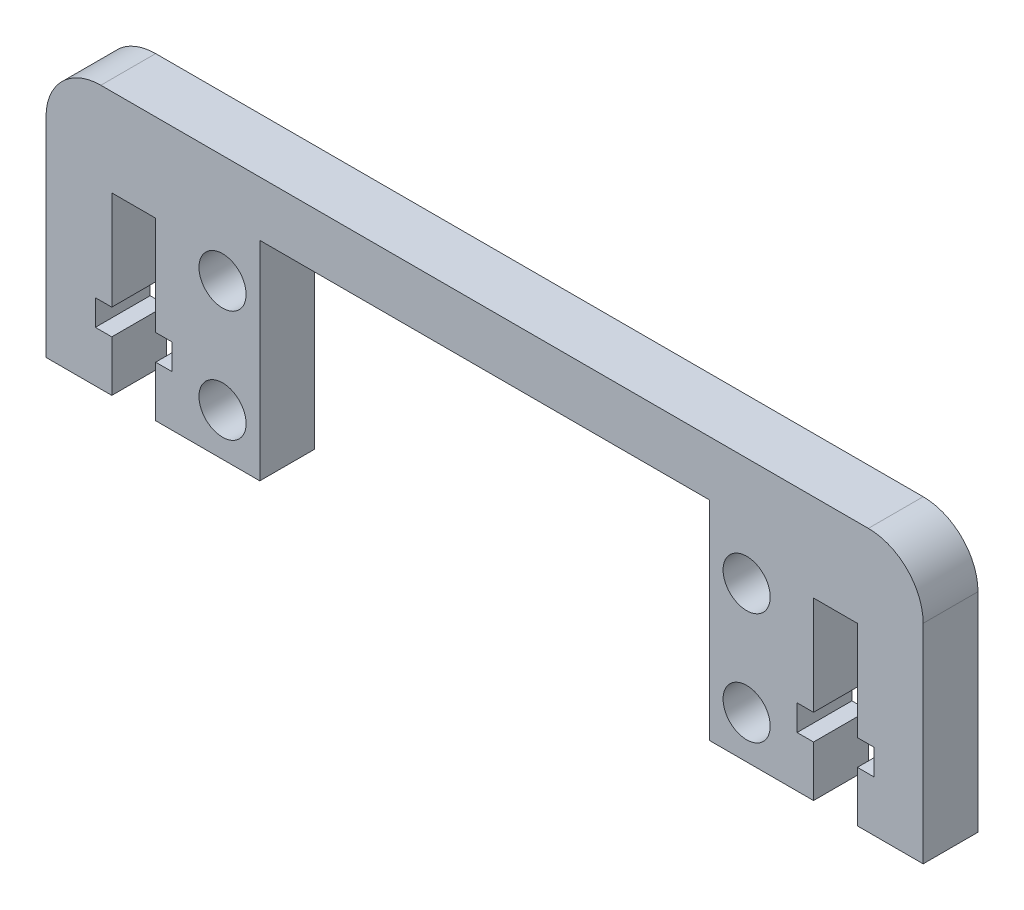
SolidWorks part; units mm, degrees
ref_plane "Front Plane" through (0, 0, 0) normal (0, 0, 1) x (1, 0, 0)
ref_plane "Top Plane" through (0, 0, 0) normal (0, 1, 0) x (1, 0, 0)
ref_plane "Right Plane" through (0, 0, 0) normal (1, 0, 0) x (0, 0, -1)
sketch "Esquisse1" plane through (0, 0, 0) normal (0, 0, 1) x (1, 0, 0)
  line L5 (-19.5, 0) -> (0, 0)
  line L6 (0, 0) -> (0, 19)
  line L7 (0, 19) -> (41, 19)
  line L8 (41, 19) -> (41, 0)
  line L9 (41, 0) -> (60.5, 0)
  line L12 (60.5, 0) -> (60.5, 19)
  line L13 (55.5, 24) -> (-14.5, 24)
  line L14 (-19.5, 19) -> (-19.5, 0)
  arc A0 (-19.5, 19) -> (-14.5, 24) centre (-14.5, 19) cw
  arc A1 (60.5, 19) -> (55.5, 24) centre (55.5, 19) ccw
  circle A10 centre (44.4, 14.1) radius 2.15
  circle A11 centre (44.4, 3.9) radius 2.15
  circle A12 centre (-3.4, 14.1) radius 2.15
  circle A13 centre (-3.4, 3.9) radius 2.15
  arc A14 (46.1125, 15.4) -> (46.1125, 12.8) centre (44.4, 14.1) ccw construction
  arc A15 (46.1125, 5.2) -> (46.1125, 2.6) centre (44.4, 3.9) ccw construction
  arc A16 (-5.1125, 12.8) -> (-5.1125, 15.4) centre (-3.4, 14.1) ccw construction
  arc A17 (-5.1125, 2.6) -> (-5.1125, 5.2) centre (-3.4, 3.9) ccw construction
  dimension "D4" = 5
  dimension "D2" = 41
  dimension "D3" = 19
  dimension "D1" = 80
  dimension "D5" = 5
extrude "Boss.-Extru.1" add sketch "Esquisse1" along normal blind 5
sketch "Esquisse3" plane through (0, 0, 5) normal (0, 0, 1) x (1, 0, 0)
  line L1 (-19.5, 0) -> (0, 0) construction
  line L4 (-9.5, 3.0026) -> (-9.5, 4.6258)
  line L5 (-9.5, 4.6258) -> (-8, 4.6258)
  line L6 (-8, 4.6258) -> (-8, 6.9717)
  line L7 (-8, 6.9717) -> (-9.5, 6.9717)
  line L8 (-9.5, 6.9717) -> (-9.5, 16)
  line L9 (-9.5, 16) -> (-13.5, 16)
  line L10 (-11.5, 16) -> (-11.5, 0) construction
  line L13 (-13.5, 3.0026) -> (-13.5, 4.6258)
  line L14 (-13.5, 4.6258) -> (-15, 4.6258)
  line L15 (-15, 4.6258) -> (-15, 6.9717)
  line L16 (-15, 6.9717) -> (-13.5, 6.9717)
  line L17 (-13.5, 6.9717) -> (-13.5, 16)
  line L18 (20.5, 24) -> (20.5, 0) construction
  line L19 (55.5, 24) -> (-14.5, 24) construction
  line L20 (52.5, 16) -> (52.5, 0) construction
  line L37 (-9.5, 3.0026) -> (-9.5, 0)
  line L38 (-13.5, 3.0026) -> (-13.5, 0)
  line L39 (-13.5, 0) -> (-9.5, 0)
  line L40 (54.5, 0) -> (50.5, 0)
  line L41 (54.5, 3.0026) -> (54.5, 0)
  line L42 (50.5, 3.0026) -> (50.5, 0)
  line L43 (54.5, 6.9717) -> (54.5, 16)
  line L44 (56, 6.9717) -> (54.5, 6.9717)
  line L45 (56, 4.6258) -> (56, 6.9717)
  line L46 (54.5, 4.6258) -> (56, 4.6258)
  line L47 (54.5, 3.0026) -> (54.5, 4.6258)
  line L48 (50.5, 16) -> (54.5, 16)
  line L49 (50.5, 6.9717) -> (50.5, 16)
  line L50 (49, 6.9717) -> (50.5, 6.9717)
  line L51 (49, 4.6258) -> (49, 6.9717)
  line L52 (50.5, 4.6258) -> (49, 4.6258)
  line L53 (50.5, 3.0026) -> (50.5, 4.6258)
  line L54 (41, 0) -> (60.5, 0) construction
  point P38 (68.2194, -16.095)
  point P39 (69.5977, -24.9342)
  point P40 (49, 5.7987)
  point P41 (71.8117, -20.1004)
  point P42 (52.458, 0)
  point P43 (48.6716, 5.2393)
  point P44 (48, 6.9717)
  point P47 (17.6722, 12.0245)
  dimension "D1" = 4
  dimension "D2" = 32
  dimension "D4" = 7
  dimension "D5" = 2.3459
  dimension "D6" = 4.6258
  dimension "D7" = 16
  dimension "D8" = 4
extrude "Enlèv. mat.-Extru.2" cut sketch "Esquisse3" against normal blind 30
